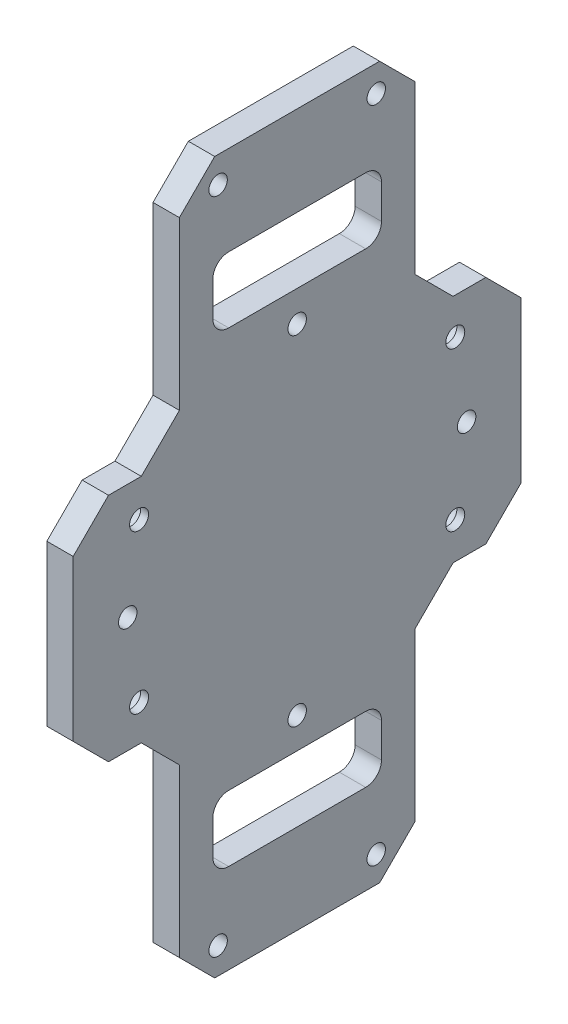
SolidWorks part; units mm, degrees
ref_plane "Front Plane" through (0, 0, 0) normal (1, 0, 0) x (0, 1, 0)
ref_plane "Top Plane" through (0, 0, 0) normal (0, 0, 1) x (0, 1, 0)
ref_plane "Right Plane" through (0, 0, 0) normal (0, 1, 0) x (-1, 0, 0)
sketch "Sketch1" plane through (0, 0, 0) normal (1, 0, 0) x (0, 1, 0)
  line L0 (0, 0) -> (0, 90) construction
  line L5 (0, 0) -> (-90, 0) construction
  line L6 (-67.5, -15.65) -> (-67.5, 15.65)
  line L7 (-60.8, 22.35) -> (-29.1274, 22.35)
  line L8 (-29.1274, 22.35) -> (-21.9, 29.5774)
  line L10 (29.1274, 22.35) -> (21.9, 29.5774)
  line L11 (60.8, 22.35) -> (29.1274, 22.35)
  line L12 (67.5, -15.65) -> (67.5, 15.65)
  line L14 (29.1274, -22.35) -> (21.9, -29.5774)
  line L15 (60.8, -22.35) -> (29.1274, -22.35)
  line L16 (-29.1274, -22.35) -> (-21.9, -29.5774)
  line L17 (-60.8, -22.35) -> (-29.1274, -22.35)
  line L18 (41, -16) -> (47.5, -16)
  line L19 (-41, -16) -> (-47.5, -16)
  line L20 (-38, -13) -> (-38, 13)
  line L21 (-41, 16) -> (-47.5, 16)
  line L22 (-50.5, -13) -> (-50.5, 13)
  line L23 (50.5, -13) -> (50.5, 13)
  line L24 (41, 16) -> (47.5, 16)
  line L25 (38, -13) -> (38, 13)
  line L26 (-67.5, -15.65) -> (-60.8, -22.35)
  line L27 (-67.5, 15.65) -> (-60.8, 22.35)
  line L28 (67.5, 15.65) -> (60.8, 22.35)
  line L29 (67.5, -15.65) -> (60.8, -22.35)
  line L30 (-21.9, 29.5774) -> (-21.9, 35.8)
  line L31 (-15.2, 42.5) -> (15.2, 42.5)
  line L32 (21.9, 29.5774) -> (21.9, 35.8)
  line L33 (-21.9, -29.5774) -> (-21.9, -35.8)
  line L34 (-15.2, -42.5) -> (15.2, -42.5)
  line L35 (21.9, -29.5774) -> (21.9, -35.8)
  line L36 (-21.9, 35.8) -> (-15.2, 42.5)
  line L37 (21.9, 35.8) -> (15.2, 42.5)
  line L38 (15.2, -42.5) -> (21.9, -35.8)
  line L39 (-21.9, -35.8) -> (-15.2, -42.5)
  line L40 (-62.5, 15) -> (-62.5, -15) construction
  line L41 (-32.15, 0) -> (0, 32.15) construction
  line L42 (0, 32.15) -> (32.15, 0) construction
  line L43 (32.15, 0) -> (0, -32.15) construction
  line L44 (0, -32.15) -> (-32.15, 0) construction
  line L45 (-15, 30) -> (15, 30) construction
  line L46 (15, 30) -> (15, -30) construction
  line L47 (15, -30) -> (-15, -30) construction
  line L48 (-15, -30) -> (-15, 30) construction
  arc A0 (41, -16) -> (38, -13) centre (41, -13) cw
  arc A1 (47.5, -16) -> (50.5, -13) centre (47.5, -13) ccw
  arc A2 (50.5, 13) -> (47.5, 16) centre (47.5, 13) ccw
  arc A3 (41, 16) -> (38, 13) centre (41, 13) ccw
  arc A4 (-47.5, -16) -> (-50.5, -13) centre (-47.5, -13) cw
  arc A5 (-41, -16) -> (-38, -13) centre (-41, -13) ccw
  arc A6 (-38, 13) -> (-41, 16) centre (-41, 13) ccw
  arc A7 (-47.5, 16) -> (-50.5, 13) centre (-47.5, 13) ccw
  circle A8 centre (0, 32.15) radius 1.75
  circle A9 centre (-32.15, 0) radius 1.75
  circle A10 centre (0, -32.15) radius 1.75
  circle A11 centre (32.15, 0) radius 1.75
  circle A12 centre (-62.5, -15) radius 1.75
  circle A13 centre (-62.5, 15) radius 1.75
  circle A14 centre (62.5, -15) radius 1.75
  circle A15 centre (62.5, 15) radius 1.75
  circle A16 centre (-15, 30) radius 1.7985
  circle A17 centre (15, 30) radius 1.7985
  circle A18 centre (15, -30) radius 1.7985
  circle A19 centre (-15, -30) radius 1.7985
  point P2 (-50.5, 0)
  point P4 (-67.5, 22.35)
  point P10 (67.5, 22.35)
  point P18 (67.5, -22.35)
  point P20 (-67.5, -22.35)
  point P39 (38, -16)
  point P42 (50.5, -16)
  point P45 (50.5, 16)
  point P48 (38, 16)
  point P51 (-50.5, -16)
  point P54 (-38, -16)
  point P57 (-38, 16)
  point P60 (-50.5, 16)
  point P72 (21.9, 42.5)
  point P73 (-21.9, -42.5)
  point P74 (-21.9, 42.5)
  point P76 (21.9, -42.5)
  point P77 (-62.5, 0)
  point P94 (-15.2, 27.4125)
  point P95 (-15, 0)
  point P96 (14.0136, 29.5774)
  point P97 (0, 30)
  dimension "D10" = 3
  dimension "D11" = 3.5
  dimension "D12" = 30
  dimension "D13" = 64.3
  dimension "D16" = 60
  dimension "D17" = 5
  dimension "D1" = 90
  dimension "D2" = 72.8
  dimension "D3" = 43.8
  dimension "D4" = 44.7
  dimension "D5" = 135
  dimension "D6" = 135
  dimension "D7" = 32
  dimension "D8" = 76
  dimension "D9" = 101
  dimension "D14" = 32.15
  dimension "D15" = 85
  dimension "D18" = 30
extrude "Boss-Extrude1" add sketch "Sketch1" along normal blind 5
sketch "Sketch2" plane through (0, 0, 0) normal (-1, 0, 0) x (0, -1, 0)
  circle A0 centre (-15, -30) radius 1.7985 construction
  circle A1 centre (15, -30) radius 1.7985 construction
  circle A2 centre (15, 30) radius 1.7985 construction
  circle A3 centre (-15, 30) radius 1.7985 construction
  circle A4 centre (-15, -30) radius 1.7985 construction
  circle A5 centre (15, -30) radius 1.7985 construction
  circle A6 centre (15, 30) radius 1.7985 construction
  circle A7 centre (-15, 30) radius 1.7985 construction
  circle A8 centre (-15, 30) radius 2.65
  circle A9 centre (15, 30) radius 2.65
  circle A10 centre (15, -30) radius 2.65
  circle A11 centre (-15, -30) radius 2.65
  dimension "D1" = 5.3
extrude "Cut-Extrude1" cut sketch "Sketch2" against normal blind 3.5
